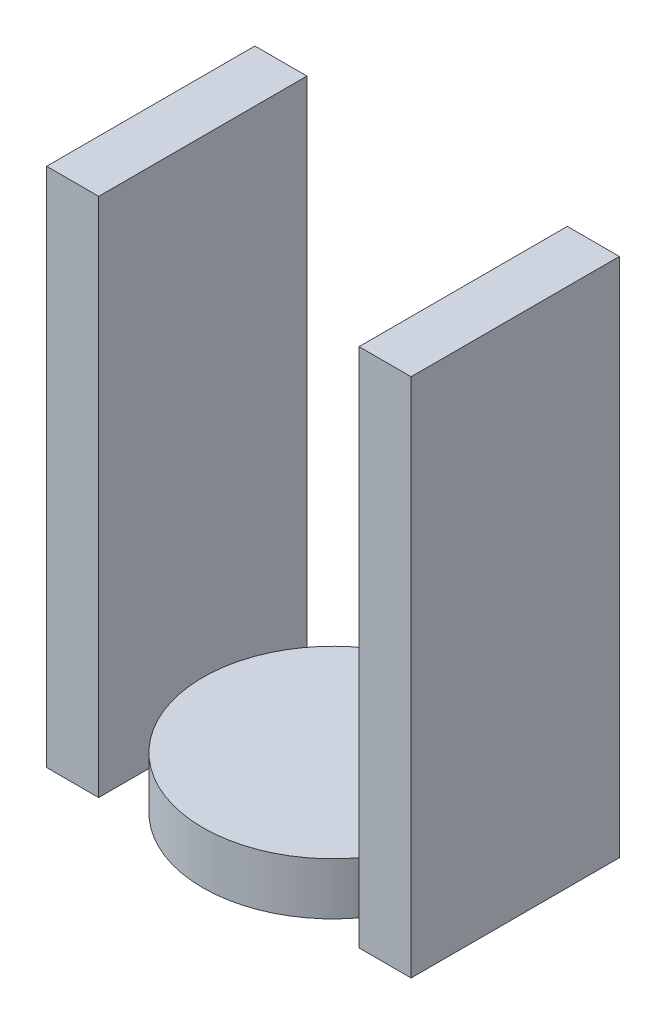
SolidWorks part; units mm, degrees
ref_plane "Front Plane" through (0, 0, 0) normal (0, 0, 1) x (1, 0, 0)
ref_plane "Top Plane" through (0, 0, 0) normal (0, 1, 0) x (1, 0, 0)
ref_plane "Right Plane" through (0, 0, 0) normal (1, 0, 0) x (0, 0, -1)
sketch "Sketch1" plane through (0, 0, 0) normal (0, 1, 0) x (1, 0, 0)
  circle A0 centre (0, 0) radius 12.5
  dimension "D1" = 25
extrude "Boss-Extrude1" add sketch "Sketch1" along normal blind 5
sketch "Sketch2" plane through (0, 0, 0) normal (0, 1, 0) x (1, 0, 0)
  line L1 (-17.5, 10) -> (-12.5, 10)
  line L2 (-17.5, 10) -> (-17.5, -10)
  line L3 (-17.5, -10) -> (-12.5, -10)
  line L4 (-12.5, 10) -> (-12.5, -10)
  line L5 (17.5, 10) -> (12.5, 10)
  line L6 (17.5, 10) -> (17.5, -10)
  line L7 (17.5, -10) -> (12.5, -10)
  line L8 (12.5, 10) -> (12.5, -10)
  circle A0 centre (0, 0) radius 12.5 construction
  dimension "D1" = 5
  dimension "D2" = 5
  dimension "D3" = 20
  dimension "D4" = 12.5
  dimension "D5" = 10
  dimension "D6" = 10
  dimension "D7" = 20
  dimension "D8" = 12.5
extrude "Boss-Extrude2" add sketch "Sketch2" along normal blind 50
